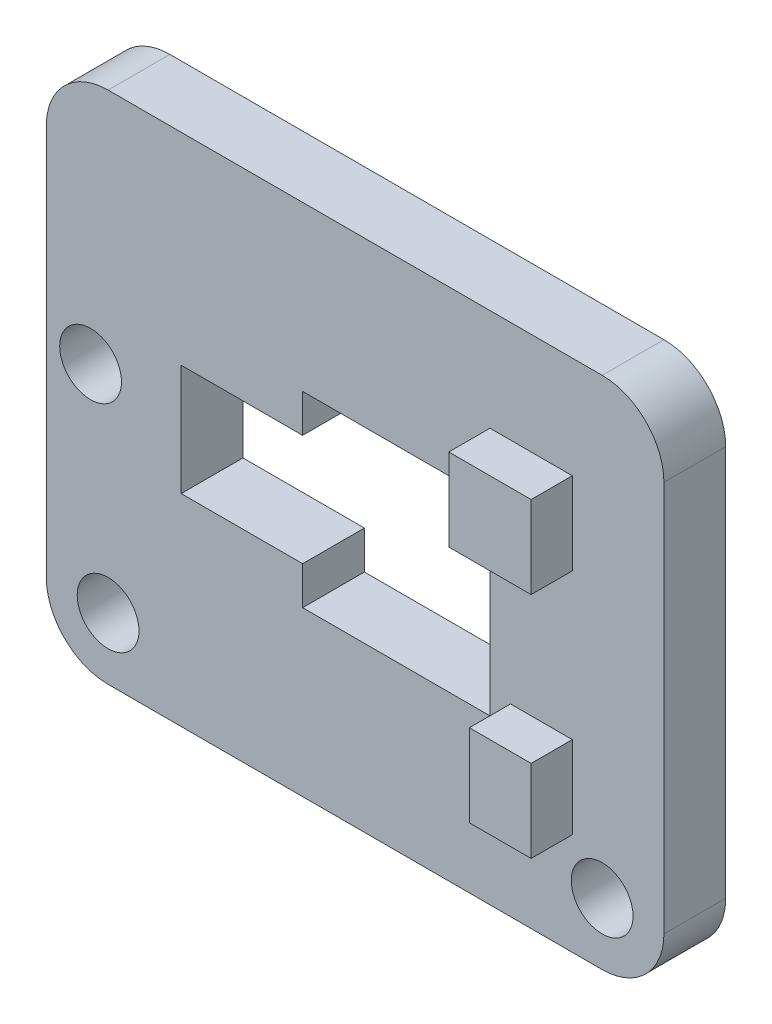
SolidWorks part; units mm, degrees
ref_plane "前视基准面" through (0, 0, 0) normal (0, 0, 1) x (1, 0, 0)
ref_plane "上视基准面" through (0, 0, 0) normal (0, 1, 0) x (1, 0, 0)
ref_plane "右视基准面" through (0, 0, 0) normal (1, 0, 0) x (0, 0, -1)
sketch "草图1" plane through (0, 0, 0) normal (0, 0, 1) x (1, 0, 0)
  line L1 (15, -12.5) -> (-15, -12.5)
  line L2 (15, -12.5) -> (15, 12.5)
  line L3 (15, 12.5) -> (-15, 12.5)
  line L4 (-15, -12.5) -> (-15, 12.5)
  line L5 (15, -12.5) -> (-15, 12.5) construction
  line L6 (15, 12.5) -> (-15, -12.5) construction
  point P0 (0, 0)
  dimension "D1" = 30
  dimension "D2" = 25
extrude "凸台-拉伸1" add sketch "草图1" along normal blind 3
sketch "草图2" plane through (0, 0, 3) normal (0, 0, 1) x (1, 0, 0)
  line L0 (0, 0) -> (15, 0) construction
  line L1 (15, -12.5) -> (15, 12.5) construction
  line L2 (6.55, 0) -> (6.55, 4.55)
  line L3 (6.55, 4.55) -> (-2.55, 4.55)
  line L4 (-2.55, 4.55) -> (-2.55, 2.7)
  line L5 (-2.55, 2.7) -> (-8.45, 2.7)
  line L6 (-8.45, 2.7) -> (-8.45, 0)
  line L8 (-8.45, 0) -> (-8.45, -2.7)
  line L9 (-8.45, -2.7) -> (-2.55, -2.7)
  line L10 (-2.55, -2.7) -> (-2.55, -4.55)
  line L11 (-2.55, -4.55) -> (6.55, -4.55)
  line L12 (6.55, -4.55) -> (6.55, 0)
  dimension "D1" = 8.45
  dimension "D2" = 9.1
  dimension "D3" = 15
  dimension "D4" = 4.55
  dimension "D5" = 2.7
extrude "切除-拉伸1" cut sketch "草图2" against normal through all
sketch "草图3" plane through (0, 0, 3) normal (0, 0, 1) x (1, 0, 0)
  line L1 (10.55, -7.55) -> (-10.55, -7.55) construction
  line L2 (10.55, -7.55) -> (10.55, 7.55) construction
  line L3 (10.55, 7.55) -> (-10.55, 7.55) construction
  line L4 (-10.55, -7.55) -> (-10.55, 7.55) construction
  line L5 (10.55, -7.55) -> (-10.55, 7.55) construction
  line L6 (10.55, 7.55) -> (-10.55, -7.55) construction
  line L7 (10.55, 7.55) -> (6.55, 7.55)
  line L8 (10.55, 7.55) -> (10.55, 3.55)
  line L9 (10.55, 3.55) -> (6.55, 3.55)
  line L10 (6.55, 7.55) -> (6.55, 3.55)
  line L11 (10.55, -7.55) -> (7.55, -7.55)
  line L12 (10.55, -7.55) -> (10.55, -3.55)
  line L13 (10.55, -3.55) -> (7.55, -3.55)
  line L14 (7.55, -7.55) -> (7.55, -3.55)
  point P0 (0, 0)
  dimension "D1" = 21.1
  dimension "D2" = 15.1
  dimension "D3" = 4
  dimension "D4" = 4
  dimension "D5" = 4
  dimension "D6" = 3
extrude "凸台-拉伸2" add sketch "草图3" along normal blind 2
fillet "圆角1" radius 3 4 edges at (-15, 12.5, 1.5) (15, 12.5, 1.5) (15, -12.5, 1.5) (-15, -12.5, 1.5)
sketch "草图4" plane through (0, 0, 0) normal (0, 0, -1) x (-1, 0, 0)
  line L0 (-12, 12.5) -> (12, 12.5) construction
  line L1 (-15, -9.5) -> (-15, 9.5) construction
  line L2 (0, 2.75) -> (0, -2.75) construction
  line L3 (2.75, 0) -> (-2.75, 0) construction
  circle A0 centre (-12, 9.5) radius 1.5
  circle A1 centre (12, 9.5) radius 1.5
  circle A2 centre (12, -9.5) radius 1.5
  circle A3 centre (-12, -9.5) radius 1.5
  dimension "D1" = 3
  dimension "D2" = 3
  dimension "D3" = 3
extrude "切除-拉伸2" cut sketch "草图4" against normal through all contours A2 | A3
sketch "草图5" plane through (0, 0, 0) normal (0, 0, -1) x (-1, 0, 0)
  circle A0 centre (12.85, 0.55) radius 1.5
  dimension "D1" = 3
extrude "切除-拉伸3" cut sketch "草图5" against normal blind 8
